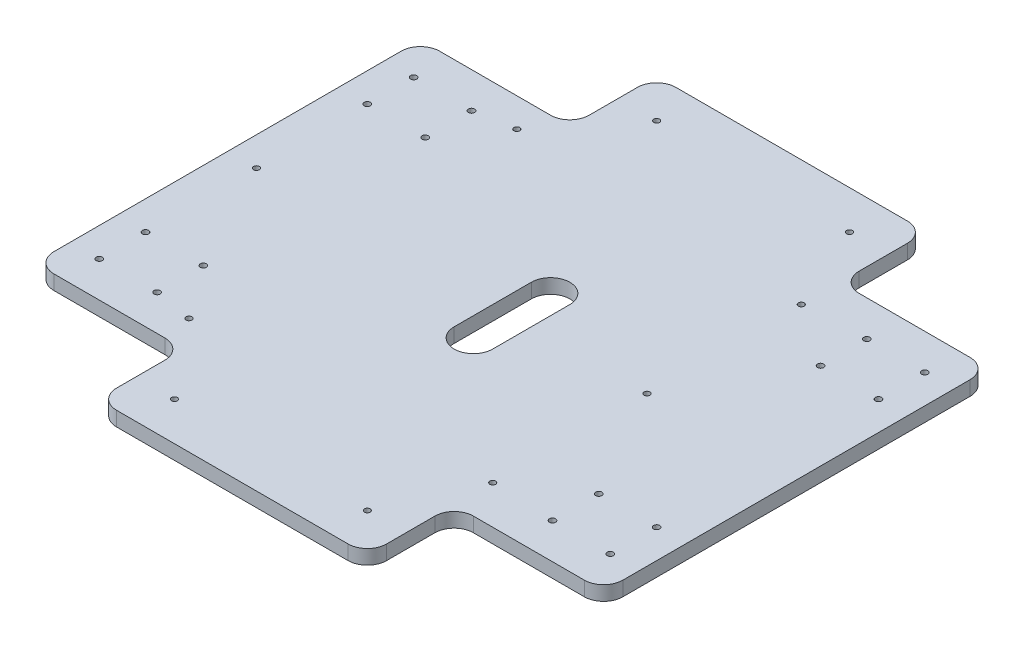
SolidWorks part; units mm, degrees
ref_plane "前视基准面" through (0, 0, 0) normal (0, 0, 1) x (1, 0, 0)
ref_plane "上视基准面" through (0, 0, 0) normal (0, 1, 0) x (1, 0, 0)
ref_plane "右视基准面" through (0, 0, 0) normal (1, 0, 0) x (0, 0, -1)
sketch "草图1" plane through (0, 0, 0) normal (0, 1, 0) x (1, 0, 0)
  line L1 (-150, 150) -> (150, 150)
  line L2 (-150, 150) -> (-150, -150)
  line L3 (-150, -150) -> (150, -150)
  line L4 (150, 150) -> (150, -150)
  line L5 (-150, 150) -> (150, -150) construction
  line L6 (-150, -150) -> (150, 150) construction
  point P0 (0, 0)
  dimension "D1" = 300
  dimension "D2" = 300
extrude "凸台-拉伸1" add sketch "草图1" along normal blind 7.5
sketch "草图2" plane through (0, 0, 0) normal (0, -1, 0) x (-1, 0, 0)
  line L0 (-207.2489, 0) -> (207.5166, 0) construction
  line L1 (0, -223.7694) -> (0, 371.3951) construction
  line L2 (-150, -100) -> (-70, -100)
  line L3 (-150, -150) -> (-150, 150) construction
  line L4 (150, -150) -> (-150, -150) construction
  line L5 (-150, 100) -> (-70, 100)
  line L6 (-150, 150) -> (150, 150) construction
  line L7 (150, -100) -> (70, -100)
  line L8 (150, 150) -> (150, -150) construction
  line L9 (150, 100) -> (70, 100)
  line L10 (-70, 100) -> (-70, 150)
  line L11 (-70, 150) -> (-150, 150)
  line L12 (70, 150) -> (70, 100)
  line L13 (-70, -100) -> (-70, -150)
  line L14 (-70, -150) -> (-150, -150)
  line L15 (-150, -150) -> (-150, -100)
  line L16 (-150, 150) -> (-150, 100)
  line L17 (70, 150) -> (150, 150)
  line L18 (150, 150) -> (150, 100)
  line L19 (70, -100) -> (70, -150)
  line L20 (70, -150) -> (150, -150)
  line L21 (150, -150) -> (150, -100)
  dimension "D1" = 50
  dimension "D2" = 50
  dimension "D3" = 80
  dimension "D4" = 80
  dimension "D5" = 80
  dimension "D6" = 80
extrude "切除-拉伸1" cut sketch "草图2" against normal blind 50
sketch "草图3" plane through (0, 0, 0) normal (0, -1, 0) x (1, 0, 0)
  circle A0 centre (132.5, 81.5057) radius 1.6
  circle A1 centre (132.5, 57.5057) radius 1.6
  circle A2 centre (102.5, 81.5057) radius 1.6
  circle A3 centre (102.5, 57.5057) radius 1.6
  circle A4 centre (-102.5, 81.5057) radius 1.6
  circle A5 centre (-102.5, 57.5057) radius 1.6
  circle A6 centre (-132.5, 81.5057) radius 1.6
  circle A7 centre (-132.5, 57.5057) radius 1.6
  circle A8 centre (-132.5, -57.5057) radius 1.6
  circle A9 centre (-132.5, -81.5057) radius 1.6
  circle A10 centre (-102.5, -57.5057) radius 1.6
  circle A11 centre (-102.5, -81.5057) radius 1.6
  circle A12 centre (132.5, -81.5057) radius 1.6
  circle A13 centre (132.5, -57.5057) radius 1.6
  circle A14 centre (102.5, -57.5057) radius 1.6
  circle A15 centre (102.5, -81.5057) radius 1.6
extrude "切除-拉伸2" cut sketch "草图3" against normal blind 500
sketch "草图5" plane through (0, 0, 0) normal (0, -1, 0) x (1, 0, 0)
  line L0 (145.7796, 0) -> (141.6899, 4.0897)
  line L1 (141.6899, 4.0897) -> (141.6899, -4.0897)
  line L2 (141.6899, -4.0897) -> (145.7796, 0)
extrude "切除-拉伸4" cut sketch "草图5" against normal blind 0.01
sketch "草图6" plane through (0, 7.5, 0) normal (0, 1, 0) x (1, 0, 0)
  line L0 (-70, 150) -> (70, 150)
  line L1 (70, 150) -> (70, 145)
  line L2 (70, 150) -> (70, 100) construction
  line L3 (70, 145) -> (-70, 145)
  line L4 (-70, 100) -> (-70, 150) construction
  line L5 (-70, 145) -> (-70, 150)
  dimension "D1" = 5
extrude "切除-拉伸5" cut sketch "草图6" against normal blind 400
sketch "草图7" plane through (0, 7.5, 0) normal (0, 1, 0) x (1, 0, 0)
  line L0 (-70, -150) -> (70, -150)
  line L1 (70, -150) -> (70, -145)
  line L2 (70, -100) -> (70, -150) construction
  line L3 (70, -145) -> (-70, -145)
  line L4 (-70, -150) -> (-70, -100) construction
  line L5 (-70, -145) -> (-70, -150)
  dimension "D1" = 5
extrude "切除-拉伸6" cut sketch "草图7" against normal blind 500
sketch "草图8" plane through (0, 7.5, 0) normal (0, 1, 0) x (1, 0, 0)
  line L0 (-150, 100) -> (-150, -100)
  line L1 (-150, -100) -> (-147.5, -100)
  line L2 (-70, -100) -> (-150, -100) construction
  line L3 (-147.5, -100) -> (-147.5, 100)
  line L4 (-150, 100) -> (-70, 100) construction
  line L5 (-147.5, 100) -> (-150, 100)
  dimension "D1" = 2.5
extrude "切除-拉伸7" cut sketch "草图8" against normal blind 500
sketch "草图9" plane through (0, 7.5, 0) normal (0, 1, 0) x (1, 0, 0)
  line L0 (150, -100) -> (70, -100) construction
  line L1 (150, 100) -> (147.5, 100)
  line L2 (150, 100) -> (150, -100)
  line L3 (150, -100) -> (147.5, -100)
  line L4 (147.5, 100) -> (147.5, -100)
  dimension "D1" = 2.5
extrude "切除-拉伸8" cut sketch "草图9" against normal blind 500
fillet "圆角1" radius 10 2 edges at (70, 3.75, 145) (-70, 3.75, 145)
fillet "圆角2" radius 10 2 edges at (-70, 3.75, 100) (70, 3.75, 100)
fillet "圆角3" radius 10 2 edges at (147.5, 3.75, 100) (-147.5, 3.75, 100)
fillet "圆角4" radius 10 2 edges at (147.5, 3.75, -100) (-147.5, 3.75, -100)
fillet "圆角5" radius 10 2 edges at (-70, 3.75, -100) (70, 3.75, -100)
fillet "圆角6" radius 10 2 edges at (70, 3.75, -145) (-70, 3.75, -145)
sketch "草图11" plane through (0, 0, 0) normal (0, -1, 0) x (1, 0, 0)
  circle A0 centre (-50, 125) radius 1.5
extrude "切除-拉伸9" cut sketch "草图11" against normal blind 500
sketch "草图12" plane through (0, 0, 0) normal (0, -1, 0) x (1, 0, 0)
  circle A0 centre (50, 125) radius 1.5
  circle A1 centre (70, 80) radius 1.5
  circle A2 centre (70, 0) radius 1.5
  circle A3 centre (70, -80) radius 1.5
  circle A4 centre (50, -125) radius 1.5
  circle A5 centre (-50, -125) radius 1.5
  circle A6 centre (-82.5, -85) radius 1.5
  circle A7 centre (-132.5, 0) radius 1.5
  circle A8 centre (-50, 125) radius 1.5
  circle A9 centre (-82.5, 85) radius 1.5
extrude "切除-拉伸10" cut sketch "草图12" against normal blind 500
sketch "草图13" plane through (0, 7.5, 0) normal (0, 1, 0) x (1, 0, 0)
  line L0 (0, 223.8035) -> (0, -237.5015) construction
  line L1 (0, -20) -> (0, 20) construction
  line L4 (-10, -20) -> (-10, 20)
  line L5 (10, -20) -> (10, 20)
  arc A2 (-10, -20) -> (10, -20) centre (0, -20) ccw
  arc A3 (10, 20) -> (-10, 20) centre (0, 20) ccw
  point P5 (0, 0)
  dimension "D1" = 40
  dimension "D2" = 20
extrude "切除-拉伸11" cut sketch "草图13" against normal blind 50
